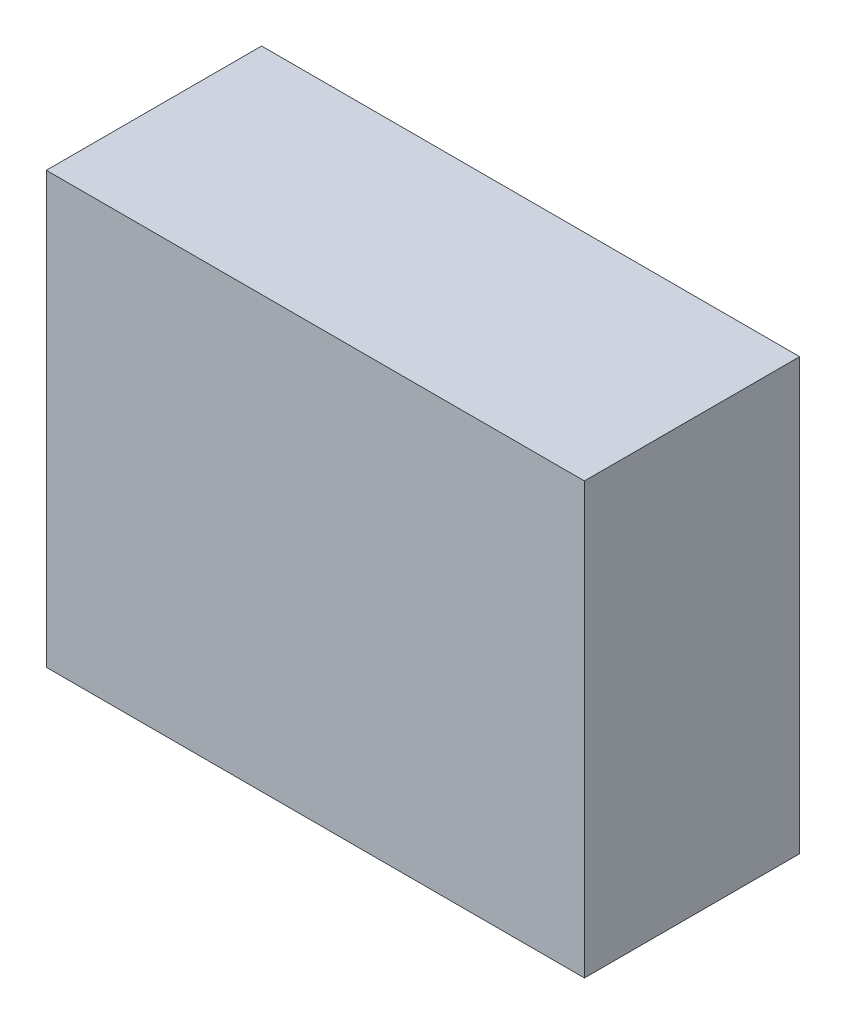
SolidWorks part; units mm, degrees
ref_plane "前视基准面" through (0, 0, 0) normal (0, 0, 1) x (1, 0, 0)
ref_plane "上视基准面" through (0, 0, 0) normal (0, 1, 0) x (1, 0, 0)
ref_plane "右视基准面" through (0, 0, 0) normal (1, 0, 0) x (0, 0, -1)
other "Configuration Table"
sketch "草图1" plane through (0, 0, 0) normal (0, 0, 1) x (1, 0, 0)
  line L1 (-25, -20) -> (25, -20)
  line L2 (-25, -20) -> (-25, 20)
  line L3 (-25, 20) -> (25, 20)
  line L4 (25, -20) -> (25, 20)
  line L5 (-25, -20) -> (25, 20) construction
  line L6 (-25, 20) -> (25, -20) construction
  point P0 (0, 0)
extrude "凸台-拉伸1" add sketch "草图1" along normal blind 20
